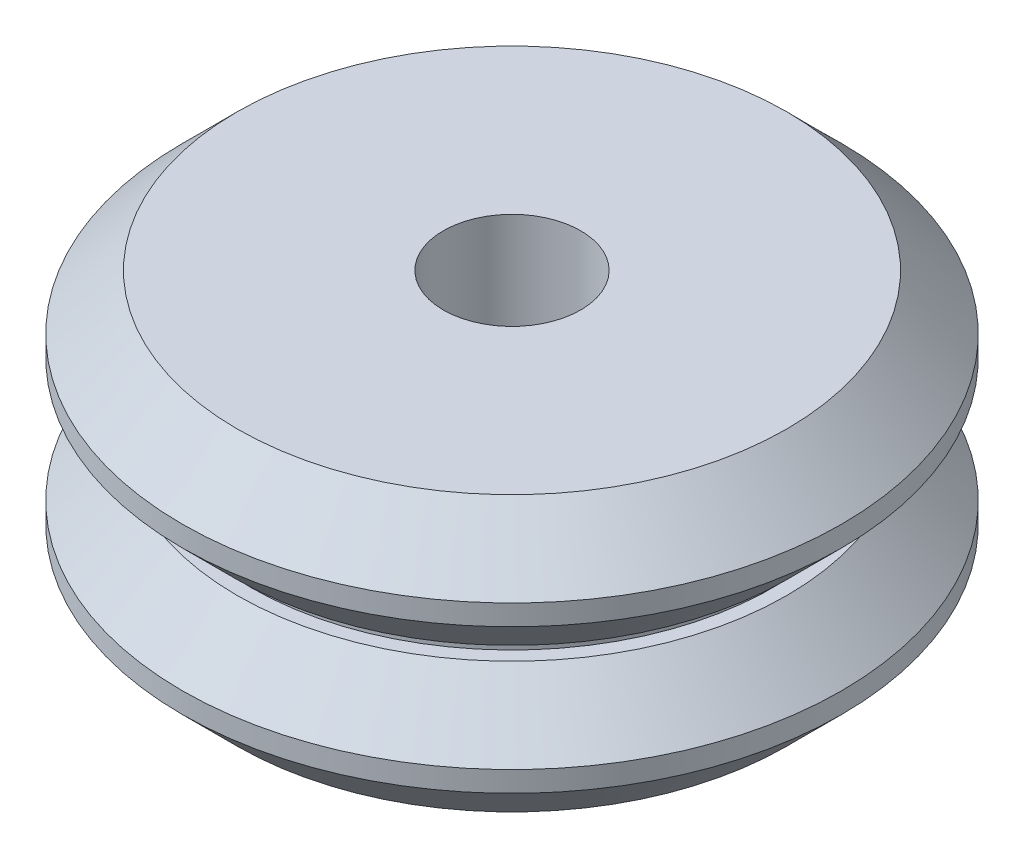
SolidWorks part; units mm, degrees
material "1.4511 (X3CrNb17)"
ref_plane "前视基准面" through (0, 0, 0) normal (0, 0, 1) x (1, 0, 0)
ref_plane "上视基准面" through (0, 0, 0) normal (0, 1, 0) x (1, 0, 0)
ref_plane "右视基准面" through (0, 0, 0) normal (1, 0, 0) x (0, 0, -1)
sketch "草图1" plane through (0, 0, 0) normal (0, 0, 1) x (1, 0, 0)
  line L0 (0, 5) -> (0, -5)
  line L1 (0, 5) -> (10, 5)
  line L2 (12, 3) -> (12, 2.25)
  line L3 (10, 0.25) -> (0, 0.25)
  line L4 (9.5, 0.25) -> (9.5, -0.25)
  line L5 (0, -0.25) -> (10, -0.25)
  line L6 (12, -2.25) -> (12, -3)
  line L7 (10, -5) -> (0, -5)
  line L8 (10, 5) -> (12, 3)
  line L9 (12, 2.25) -> (10, 0.25)
  line L10 (10, -0.25) -> (12, -2.25)
  line L11 (12, -3) -> (10, -5)
  point P0 (12, 0.25)
  point P4 (0, 0)
  point P6 (12, 5)
  point P11 (12, -0.25)
  point P12 (12, -5)
  dimension "D1" = 10
  dimension "D2" = 12
  dimension "D3" = 4.75
  dimension "D4" = 9.5
  dimension "D5" = 0.5
  dimension "D6" = 12
revolve "旋转1" add sketch "草图1" angle 360 about L0
sketch "草图2" plane through (0, 5, 0) normal (0, 1, 0) x (1, 0, 0)
  circle A0 centre (0, 0) radius 2.5
  dimension "D1" = 5
extrude "切除-拉伸1" cut sketch "草图2" against normal through all
